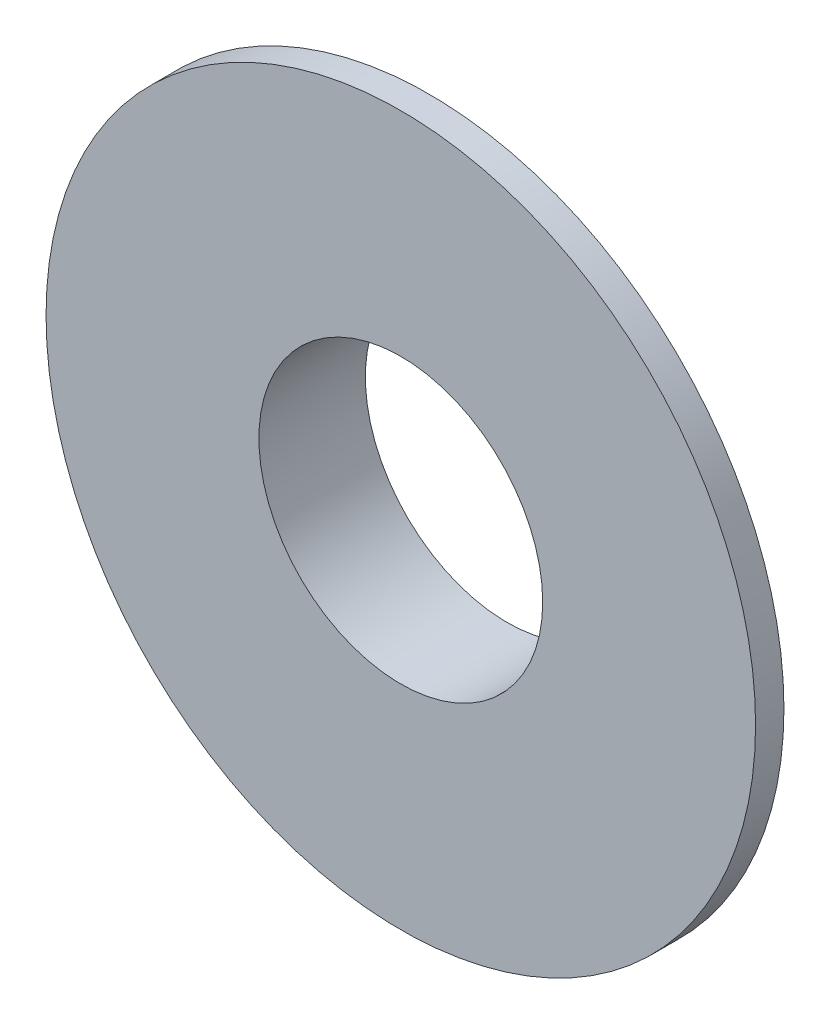
SolidWorks part; units mm, degrees
material "AISI 304"
ref_plane "Front Plane" through (0, 0, 0) normal (0, 0, 1) x (1, 0, 0)
ref_plane "Top Plane" through (0, 0, 0) normal (0, 1, 0) x (1, 0, 0)
ref_plane "Right Plane" through (0, 0, 0) normal (1, 0, 0) x (0, 0, -1)
sketch "Sketch1" plane through (0, 0, 0) normal (0, 1, 0) x (1, 0, 0)
  line L0 (0, 0) -> (0, 38.7467) construction
  line L1 (-4, 3) -> (-4, 0)
  line L2 (-4, 0) -> (-10, 0)
  line L3 (-10, 0) -> (-10, 0.8)
  line L4 (-4, 3) -> (-6.5, 3)
  line L5 (-10, 0.8) -> (-7.4128, 1.0263)
  line L6 (-6.5, 3) -> (-6.5, 2.0225)
  arc A0 (-6.5, 2.0225) -> (-7.4128, 1.0263) centre (-7.5, 2.0225) cw
  point P1 (-4, 0)
  point P4 (-10, 0)
  point P5 (-10, 0.8)
  point P6 (-6.5, 3)
  point P7 (-4, 3)
  dimension "D1" = 1
revolve "Revolve1" add sketch "Sketch1" angle 360 about L0
